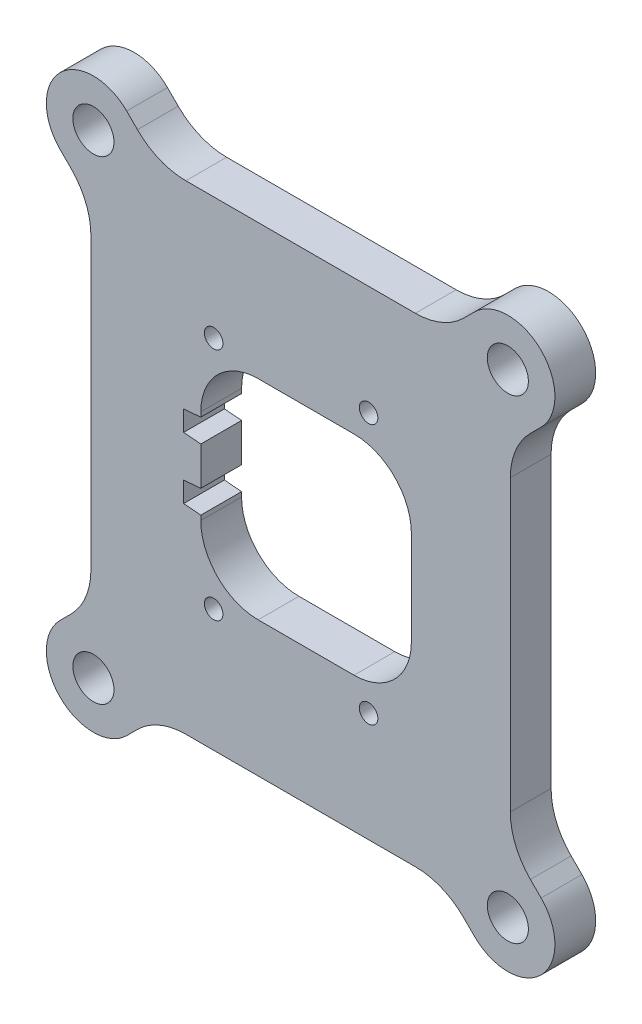
SolidWorks part; units mm, degrees
material "Custom Plastic"
ref_plane "X-Y Datum" through (0, 0, 0) normal (0, 0, 1) x (1, 0, 0)
ref_plane "X-Z Datum" through (0, 0, 0) normal (0, 1, 0) x (1, 0, 0)
ref_plane "Y-Z Datum" through (0, 0, 0) normal (1, 0, 0) x (0, 0, -1)
sketch "Sketch1" plane through (0, 0, 0) normal (0, 0, 1) x (1, 0, 0)
  line L12 (-20.3196, -31.5978) -> (-19.065, -30.3431)
  line L13 (-13.4081, -28) -> (13.4081, -28)
  line L14 (19.065, -30.3431) -> (20.3196, -31.5978)
  line L15 (28.0978, -23.8196) -> (26.8431, -22.565)
  line L16 (24.5, -16.9081) -> (24.5, 16.9081)
  line L17 (26.8431, 22.565) -> (28.0978, 23.8196)
  line L18 (20.3196, 31.5978) -> (19.065, 30.3431)
  line L19 (13.4081, 28) -> (-13.4081, 28)
  line L20 (-19.065, 30.3431) -> (-20.3196, 31.5978)
  line L21 (-28.0978, 23.8196) -> (-26.8431, 22.565)
  line L22 (-24.5, 16.9081) -> (-24.5, -16.9081)
  line L23 (-26.8431, -22.565) -> (-28.0978, -23.8196)
  line L24 (-20.3196, -31.5978) -> (-19.065, -30.3431)
  line L25 (-13.4081, -28) -> (13.4081, -28)
  line L26 (19.065, -30.3431) -> (20.3196, -31.5978)
  line L27 (28.0978, -23.8196) -> (26.8431, -22.565)
  line L28 (24.5, -16.9081) -> (24.5, 16.9081)
  line L29 (26.8431, 22.565) -> (28.0978, 23.8196)
  line L30 (20.3196, 31.5978) -> (19.065, 30.3431)
  line L31 (13.4081, 28) -> (-13.4081, 28)
  line L32 (-19.065, 30.3431) -> (-20.3196, 31.5978)
  line L33 (-28.0978, 23.8196) -> (-26.8431, 22.565)
  line L34 (-24.5, 16.9081) -> (-24.5, -16.9081)
  line L35 (-26.8431, -22.565) -> (-28.0978, -23.8196)
  arc A12 (-13.4081, -28) -> (-19.065, -30.3431) centre (-13.4081, -36) ccw
  arc A13 (19.065, -30.3431) -> (13.4081, -28) centre (13.4081, -36) ccw
  arc A14 (20.3196, -31.5978) -> (28.0978, -23.8196) centre (24.2087, -27.7087) ccw
  arc A15 (24.5, -16.9081) -> (26.8431, -22.565) centre (32.5, -16.9081) ccw
  arc A16 (26.8431, 22.565) -> (24.5, 16.9081) centre (32.5, 16.9081) ccw
  arc A17 (28.0978, 23.8196) -> (20.3196, 31.5978) centre (24.2087, 27.7087) ccw
  arc A18 (13.4081, 28) -> (19.065, 30.3431) centre (13.4081, 36) ccw
  arc A19 (-19.065, 30.3431) -> (-13.4081, 28) centre (-13.4081, 36) ccw
  arc A20 (-20.3196, 31.5978) -> (-28.0978, 23.8196) centre (-24.2087, 27.7087) ccw
  arc A21 (-24.5, 16.9081) -> (-26.8431, 22.565) centre (-32.5, 16.9081) ccw
  arc A22 (-26.8431, -22.565) -> (-24.5, -16.9081) centre (-32.5, -16.9081) ccw
  arc A23 (-28.0978, -23.8196) -> (-20.3196, -31.5978) centre (-24.2087, -27.7087) ccw
  arc A24 (-13.4081, -28) -> (-19.065, -30.3431) centre (-13.4081, -36) ccw
  arc A25 (19.065, -30.3431) -> (13.4081, -28) centre (13.4081, -36) ccw
  arc A26 (20.3196, -31.5978) -> (28.0978, -23.8196) centre (24.2087, -27.7087) ccw
  arc A27 (24.5, -16.9081) -> (26.8431, -22.565) centre (32.5, -16.9081) ccw
  arc A28 (26.8431, 22.565) -> (24.5, 16.9081) centre (32.5, 16.9081) ccw
  arc A29 (28.0978, 23.8196) -> (20.3196, 31.5978) centre (24.2087, 27.7087) ccw
  arc A30 (13.4081, 28) -> (19.065, 30.3431) centre (13.4081, 36) ccw
  arc A31 (-19.065, 30.3431) -> (-13.4081, 28) centre (-13.4081, 36) ccw
  arc A32 (-20.3196, 31.5978) -> (-28.0978, 23.8196) centre (-24.2087, 27.7087) ccw
  arc A33 (-24.5, 16.9081) -> (-26.8431, 22.565) centre (-32.5, 16.9081) ccw
  arc A34 (-26.8431, -22.565) -> (-24.5, -16.9081) centre (-32.5, -16.9081) ccw
  arc A35 (-28.0978, -23.8196) -> (-20.3196, -31.5978) centre (-24.2087, -27.7087) ccw
  point P7 (-24.2087, -27.7087)
  point P12 (-24.2087, 27.7087)
  point P17 (24.2087, -27.7087)
  point P22 (24.2087, 27.7087)
  dimension "D1" = 0
extrude "Boss-Extrude1" add sketch "Sketch1" along normal blind 4.7625
hole_wizard "M4 Clearance Hole1" positions "Sketch6" profile "Sketch3" hole size "M4" standard "ANSI Metric" end condition through all
sketch "Sketch6" plane through (0, 0, 4.7625) normal (0, 0, 1) x (1, 0, 0)
  point P0 (-24.2087, 27.7087)
  point P3 (24.2087, 27.7087)
  point P6 (24.2087, -27.7087)
  point P9 (-24.2087, -27.7087)
sketch "Sketch3" plane through (-24.2087, 27.7087, 4.7625) normal (1, 0, 0) x (0, -1, 0)
  line L0 (0, 0) -> (0, 4.7625)
  line L1 (0, 4.7625) -> (2.4, 4.7625)
  line L2 (2.4, 4.7625) -> (2.4, 0)
  line L5 (2.4, 0) -> (0, 0)
  line L11 (0, -6.35) -> (0, 107.95) construction
  dimension "Thru Hole Dia." = 4.8
  dimension "Thru Hole Depth" = 4.7625
sketch "Sketch5" plane through (0, 0, 4.7625) normal (0, 0, 1) x (1, 0, 0)
  line L0 (-4.9615, -11.7) -> (6.2385, -11.7) construction
  line L1 (12.4385, -5.5) -> (12.4385, 5.5) construction
  line L2 (6.2385, 11.7) -> (-4.9615, 11.7) construction
  line L3 (-11.1615, 5.5) -> (-11.1615, 4.5) construction
  line L4 (-10.856, 4.5267) -> (-11.3009, 4.4878) construction
  line L5 (-11.3009, 4.4878) -> (-13.1615, 4.325) construction
  line L6 (-13.1615, 4.325) -> (-13.1615, 2.875) construction
  line L7 (-11.3009, 2.7122) -> (-10.856, 2.6733) construction
  line L8 (-11.3009, 2.7122) -> (-13.1615, 2.875) construction
  line L9 (-11.1615, 2.7) -> (-11.1615, -2.7) construction
  line L10 (-10.856, -2.6733) -> (-11.3009, -2.7122) construction
  line L11 (-11.3009, -2.7122) -> (-13.1615, -2.875) construction
  line L12 (-13.1615, -2.875) -> (-13.1615, -4.325) construction
  line L13 (-11.3009, -4.4878) -> (-13.1615, -4.325) construction
  line L14 (-11.3009, -4.4878) -> (-10.856, -4.5267) construction
  line L15 (-11.1615, -4.5) -> (-11.1615, -5.5) construction
  line L16 (-4.9615, -11.7) -> (6.2385, -11.7) construction
  line L17 (12.4385, -5.5) -> (12.4385, 5.5) construction
  line L18 (6.2385, 11.7) -> (-4.9615, 11.7) construction
  line L19 (-11.1615, 5.5) -> (-11.1615, 4.5) construction
  line L20 (-10.856, 4.5267) -> (-11.3009, 4.4878) construction
  line L21 (-11.3009, 4.4878) -> (-13.1615, 4.325) construction
  line L22 (-13.1615, 4.325) -> (-13.1615, 2.875) construction
  line L23 (-11.3009, 2.7122) -> (-10.856, 2.6733) construction
  line L24 (-11.3009, 2.7122) -> (-13.1615, 2.875) construction
  line L25 (-11.1615, 2.7) -> (-11.1615, -2.7) construction
  line L26 (-10.856, -2.6733) -> (-11.3009, -2.7122) construction
  line L27 (-11.3009, -2.7122) -> (-13.1615, -2.875) construction
  line L28 (-13.1615, -2.875) -> (-13.1615, -4.325) construction
  line L29 (-11.3009, -4.4878) -> (-13.1615, -4.325) construction
  line L30 (-11.3009, -4.4878) -> (-10.856, -4.5267) construction
  line L31 (-11.1615, -4.5) -> (-11.1615, -5.5) construction
  line L32 (-11.6615, -4.5) -> (-11.6615, -5.5)
  line L33 (-4.9615, -12.2) -> (6.2385, -12.2)
  line L34 (12.9385, -5.5) -> (12.9385, 5.5)
  line L35 (6.2385, 12.2) -> (-4.9615, 12.2)
  line L36 (-11.6615, 5.5) -> (-11.6615, 4.5)
  line L37 (-10.8996, 5.0248) -> (-11.3445, 4.9859)
  line L38 (-11.3445, 4.9859) -> (-13.6615, 4.7832)
  line L39 (-13.6615, 4.7832) -> (-13.6615, 2.4168)
  line L40 (-11.3445, 2.2141) -> (-13.6615, 2.4168)
  line L41 (-11.3445, 2.2141) -> (-10.8996, 2.1752)
  line L42 (-11.6615, 2.7) -> (-11.6615, -2.7)
  line L43 (-10.8996, -2.1752) -> (-11.3445, -2.2141)
  line L44 (-11.3445, -2.2141) -> (-13.6615, -2.4168)
  line L45 (-13.6615, -2.4168) -> (-13.6615, -4.7832)
  line L46 (-11.3445, -4.9859) -> (-13.6615, -4.7832)
  line L47 (-11.3445, -4.9859) -> (-10.8996, -5.0248)
  arc A0 (6.2385, -11.7) -> (12.4385, -5.5) centre (6.2385, -5.5) ccw construction
  arc A1 (12.4385, 5.5) -> (6.2385, 11.7) centre (6.2385, 5.5) ccw construction
  arc A2 (-4.9615, 11.7) -> (-11.1615, 5.5) centre (-4.9615, 5.5) ccw construction
  arc A3 (-11.1615, -5.5) -> (-4.9615, -11.7) centre (-4.9615, -5.5) ccw construction
  arc A4 (6.2385, -11.7) -> (12.4385, -5.5) centre (6.2385, -5.5) ccw construction
  arc A5 (12.4385, 5.5) -> (6.2385, 11.7) centre (6.2385, 5.5) ccw construction
  arc A6 (-4.9615, 11.7) -> (-11.1615, 5.5) centre (-4.9615, 5.5) ccw construction
  arc A7 (-11.1615, -5.5) -> (-4.9615, -11.7) centre (-4.9615, -5.5) ccw construction
  arc A8 (-11.6615, -5.5) -> (-4.9615, -12.2) centre (-4.9615, -5.5) ccw
  arc A9 (6.2385, -12.2) -> (12.9385, -5.5) centre (6.2385, -5.5) ccw
  arc A10 (12.9385, 5.5) -> (6.2385, 12.2) centre (6.2385, 5.5) ccw
  arc A11 (-4.9615, 12.2) -> (-11.6615, 5.5) centre (-4.9615, 5.5) ccw
  arc A16 (-10.1615, -14.785) -> (-10.1615, -12.615) centre (-10.1615, -13.7) ccw construction
  arc A17 (-10.1615, -12.615) -> (-10.1615, -14.785) centre (-10.1615, -13.7) ccw construction
  arc A18 (-10.1615, -14.785) -> (-10.1615, -12.615) centre (-10.1615, -13.7) ccw
  arc A19 (-10.1615, -12.615) -> (-10.1615, -14.785) centre (-10.1615, -13.7) ccw
  arc A20 (-10.1615, 14.785) -> (-10.1615, 12.615) centre (-10.1615, 13.7) ccw construction
  arc A21 (-10.1615, 12.615) -> (-10.1615, 14.785) centre (-10.1615, 13.7) ccw construction
  arc A22 (-10.1615, 14.785) -> (-10.1615, 12.615) centre (-10.1615, 13.7) ccw
  arc A23 (-10.1615, 12.615) -> (-10.1615, 14.785) centre (-10.1615, 13.7) ccw
  arc A24 (7.9385, 16.285) -> (7.9385, 14.115) centre (7.9385, 15.2) ccw construction
  arc A25 (7.9385, 14.115) -> (7.9385, 16.285) centre (7.9385, 15.2) ccw construction
  arc A26 (7.9385, 16.285) -> (7.9385, 14.115) centre (7.9385, 15.2) ccw
  arc A27 (7.9385, 14.115) -> (7.9385, 16.285) centre (7.9385, 15.2) ccw
  arc A28 (7.9385, -16.285) -> (7.9385, -14.115) centre (7.9385, -15.2) ccw construction
  arc A29 (7.9385, -14.115) -> (7.9385, -16.285) centre (7.9385, -15.2) ccw construction
  arc A30 (7.9385, -16.285) -> (7.9385, -14.115) centre (7.9385, -15.2) ccw
  arc A31 (7.9385, -14.115) -> (7.9385, -16.285) centre (7.9385, -15.2) ccw
  dimension "D1" = 0.5
extrude "Cut-Extrude1" cut sketch "Sketch5" against normal through all
